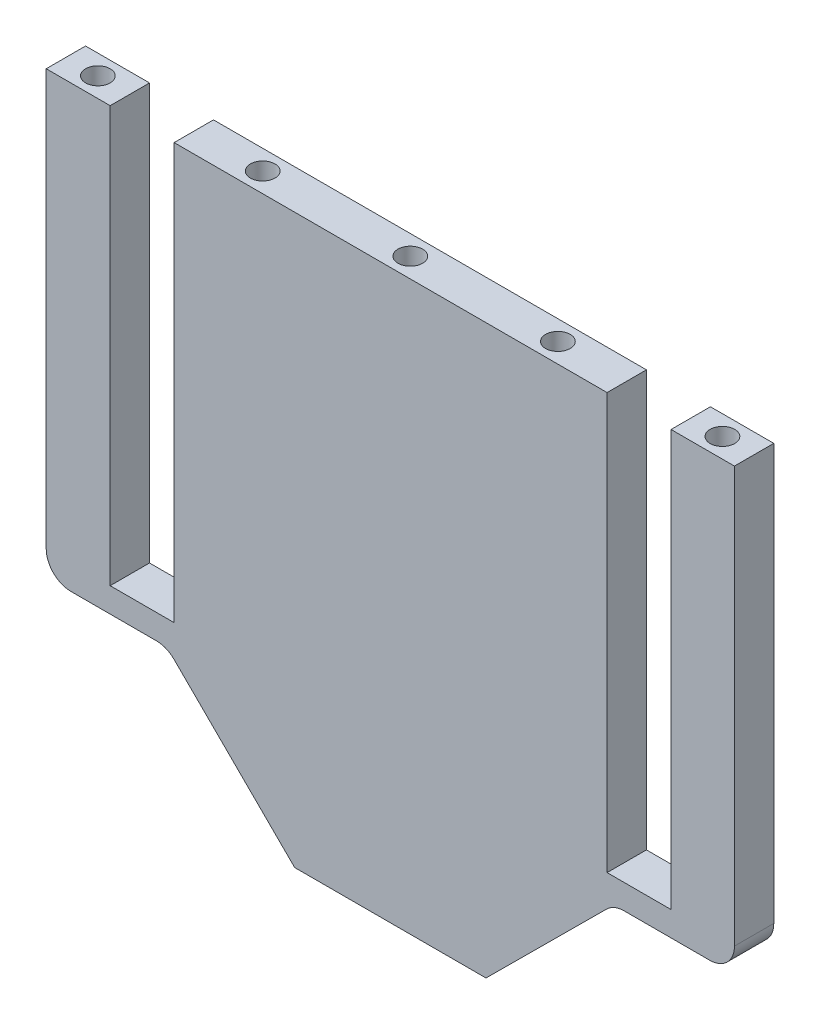
SolidWorks part; units mm, degrees
ref_plane "Front Plane" through (0, 0, 0) normal (0, 0, 1) x (1, 0, 0)
ref_plane "Top Plane" through (0, 0, 0) normal (0, 1, 0) x (1, 0, 0)
ref_plane "Right Plane" through (0, 0, 0) normal (1, 0, 0) x (0, 0, -1)
sketch "Sketch1" plane through (0, 0, 0) normal (0, 0, 1) x (1, 0, 0)
  line L0 (0, 30.8599) -> (0, 219.0089)
  line L1 (25.9628, 24.405) -> (50.5, 0)
  line L2 (59.5039, 309.9858) -> (80.3789, 309.9858)
  line L3 (134.8829, 25.8599) -> (117.446, 25.8599)
  line L5 (5, 25.8599) -> (22.4368, 25.8599)
  line L6 (96.9829, 270.8599) -> (83.9829, 270.8599) construction
  line L7 (0, 220.8599) -> (3.9, 220.8599) construction
  line L8 (3.9, 220.8599) -> (42.9, 220.8599) construction
  line L9 (42.9, 220.8599) -> (42.9, 270.8599) construction
  line L10 (96.9829, 220.8599) -> (96.9829, 270.8599) construction
  line L11 (115.3829, 25.8599) -> (89.3829, 25.8599) construction
  line L12 (24.5, 25.8599) -> (50.5, 25.8599) construction
  line L13 (0, 0) -> (0, 25.8599) construction
  line L14 (42.9, 270.8599) -> (55.9, 270.8599) construction
  line L15 (55.9, 270.8599) -> (55.9, 310) construction
  line L16 (54.8024, 306.5671) -> (43.2101, 271.7903)
  line L17 (42.2614, 270.1156) -> (1.2053, 222.2648)
  line L18 (50.5, 25.8599) -> (50.5, 0) construction
  line L20 (135.9829, 220.8599) -> (96.9829, 220.8599) construction
  line L21 (139.8829, 220.8599) -> (135.9829, 220.8599) construction
  line L22 (97.6215, 270.1156) -> (138.6775, 222.2648)
  line L23 (85.0805, 306.5671) -> (96.6727, 271.7903)
  line L24 (139.8829, 30.8599) -> (139.8829, 219.0089)
  line L25 (89.3829, 25.8599) -> (89.3829, 0) construction
  line L26 (113.92, 24.405) -> (89.3829, 0)
  line L27 (89.3829, 0) -> (50.5, 0)
  line L28 (0, 219.0089) -> (13, 219.0089) construction
  line L29 (13, 219.0089) -> (13, 30.8599)
  line L30 (13, 30.8599) -> (26, 30.8599)
  line L31 (26, 30.8599) -> (26, 219.0089)
  line L32 (26, 219.0089) -> (13, 219.0089)
  line L35 (127, 30.8599) -> (114, 30.8599)
  line L36 (114, 219.0089) -> (127, 219.0089)
  line L37 (114, 30.8599) -> (114, 219.0089)
  line L38 (127, 219.0089) -> (127, 30.8599)
  arc A0 (54.8024, 306.5671) -> (59.5039, 309.9858) centre (59.5458, 304.986) cw
  arc A1 (42.2614, 270.1156) -> (43.2101, 271.7903) centre (38.4667, 273.3715) ccw
  arc A2 (0, 219.0089) -> (1.2053, 222.2648) centre (5, 219.0089) cw
  arc A3 (85.0805, 306.5671) -> (80.3789, 309.9858) centre (80.337, 304.986) ccw
  arc A4 (139.8829, 219.0089) -> (138.6775, 222.2648) centre (134.8829, 219.0089) ccw
  arc A5 (97.6215, 270.1156) -> (96.6727, 271.7903) centre (101.4161, 273.3715) cw
  arc A6 (117.446, 25.8599) -> (113.92, 24.405) centre (117.446, 20.8599) ccw
  arc A7 (22.4368, 25.8599) -> (25.9628, 24.405) centre (22.4368, 20.8599) cw
  arc A8 (134.8829, 25.8599) -> (139.8829, 30.8599) centre (134.8829, 30.8599) ccw
  arc A9 (5, 25.8599) -> (0, 30.8599) centre (5, 30.8599) cw
  dimension "D1" = 5
  dimension "D2" = 5
  dimension "D3" = 5
extrude "Boss-Extrude1" add sketch "Sketch1" along normal blind 8
sketch "Sketch2" plane through (0, 0, 8) normal (0, 0, 1) x (1, 0, 0)
  line L2 (92.3829, 206.0089) -> (47.3829, 206.0089)
  line L3 (26, 219.0089) -> (26, 206.0089)
  line L4 (26, 30.8599) -> (26, 219.0089) construction
  line L8 (47.3829, 206.0089) -> (47.3829, 154.0089)
  line L9 (47.3829, 154.0089) -> (92.3829, 154.0089)
  line L10 (92.3829, 206.0089) -> (92.3829, 154.0089)
extrude "Cut-Extrude1" cut sketch "Sketch2" against normal through all contours L10 L2 L8 L9
sketch "Sketch3" plane through (0, 0, 0) normal (0, 0, -1) x (-1, 0, 0)
  line L1 (0, 115.3599) -> (-139.8829, 115.3599)
  line L2 (-139.8829, 30.8599) -> (-139.8829, 219.0089) construction
split "Split1" trim tools "Sketch3" bodies to split 102 resulting bodies 103 104
move or copy body "Body-Move/Copy1" bodies to move or copy 103 copy no translate (0, 34.7934, 0) parameters "D1"=0, "D2"=34.7934, "D3"=0
sketch "Sketch4" plane through (0, 150.1534, 0) normal (0, -1, 0) x (-1, 0, 0)
  circle A0 centre (-6.5, -4) radius 2.5
  circle A1 centre (-70, -4) radius 2.5
  circle A2 centre (-40, -4) radius 2.5
  circle A3 centre (-100, -4) radius 2.5
  circle A4 centre (-133.4414, -4) radius 2.5
sketch "Sketch5" plane through (0, 115.3599, -115.3599) normal (0, -1, 0) x (1, 0, 0)
  circle A0 centre (133.4414, 119.3599) radius 2.5
  circle A1 centre (70, 119.3599) radius 2.5
  circle A2 centre (100, 119.3599) radius 2.5
  circle A3 centre (40, 119.3599) radius 2.5
  circle A4 centre (6.5, 119.3599) radius 2.5
extrude "Cut-Extrude6" cut sketch "Sketch5" along normal blind 5.2
extrude "Cut-Extrude7" cut sketch "Sketch4" against normal blind 5.2
delete or keep bodies "Body-Delete/Keep 1" type delete bodies bodies 107
